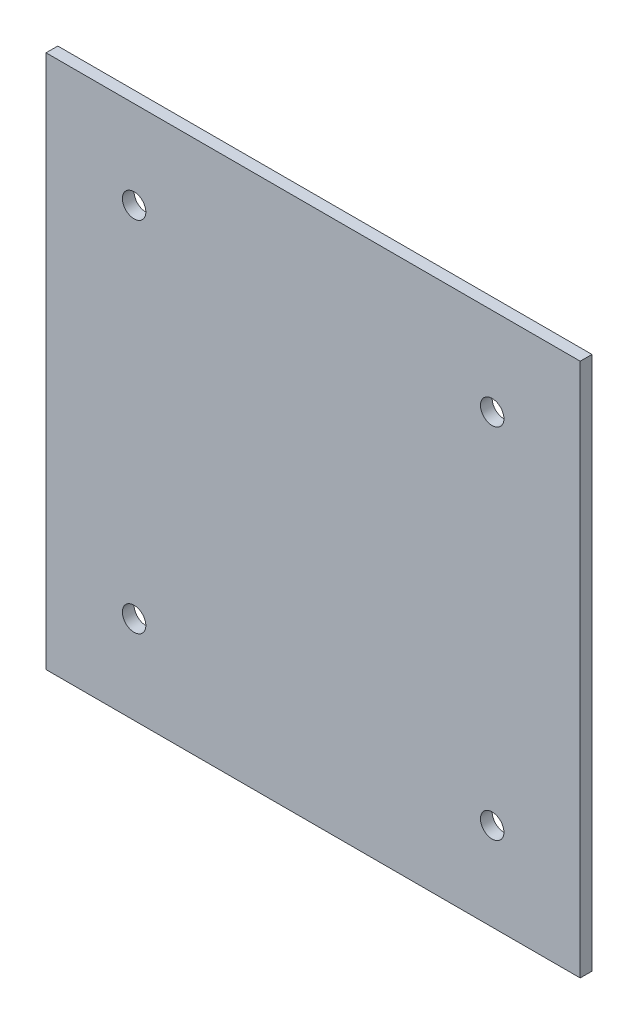
SolidWorks part; units mm, degrees
ref_plane "Alzado" through (0, 0, 0) normal (0, 0, 1) x (1, 0, 0)
ref_plane "Planta" through (0, 0, 0) normal (0, 1, 0) x (1, 0, 0)
ref_plane "Vista lateral" through (0, 0, 0) normal (1, 0, 0) x (0, 0, -1)
sketch "Croquis1" plane through (0, 0, 0) normal (0, 0, 1) x (1, 0, 0)
  line L1 (0, 0) -> (182, 0)
  line L2 (0, 0) -> (0, 182)
  line L3 (0, 182) -> (182, 182)
  line L4 (182, 0) -> (182, 182)
  dimension "D1" = 182
  dimension "D2" = 182
extrude "Saliente-Extruir1" add sketch "Croquis1" along normal mid plane 4
sketch "Croquis2" plane through (0, 0, 2) normal (0, 0, 1) x (1, 0, 0)
  line L0 (0, 182) -> (0, 0) construction
  line L1 (182, 182) -> (0, 182) construction
  circle A0 centre (30, 152) radius 4
  circle A1 centre (152, 152) radius 4
  circle A2 centre (152, 30) radius 4
  circle A3 centre (30, 30) radius 4
  dimension "D1" = 8
  dimension "D2" = 30
  dimension "D3" = 30
  dimension "D4" = 2
  dimension "D5" = 2
extrude "Cortar-Extruir1" cut sketch "Croquis2" against normal blind 4
